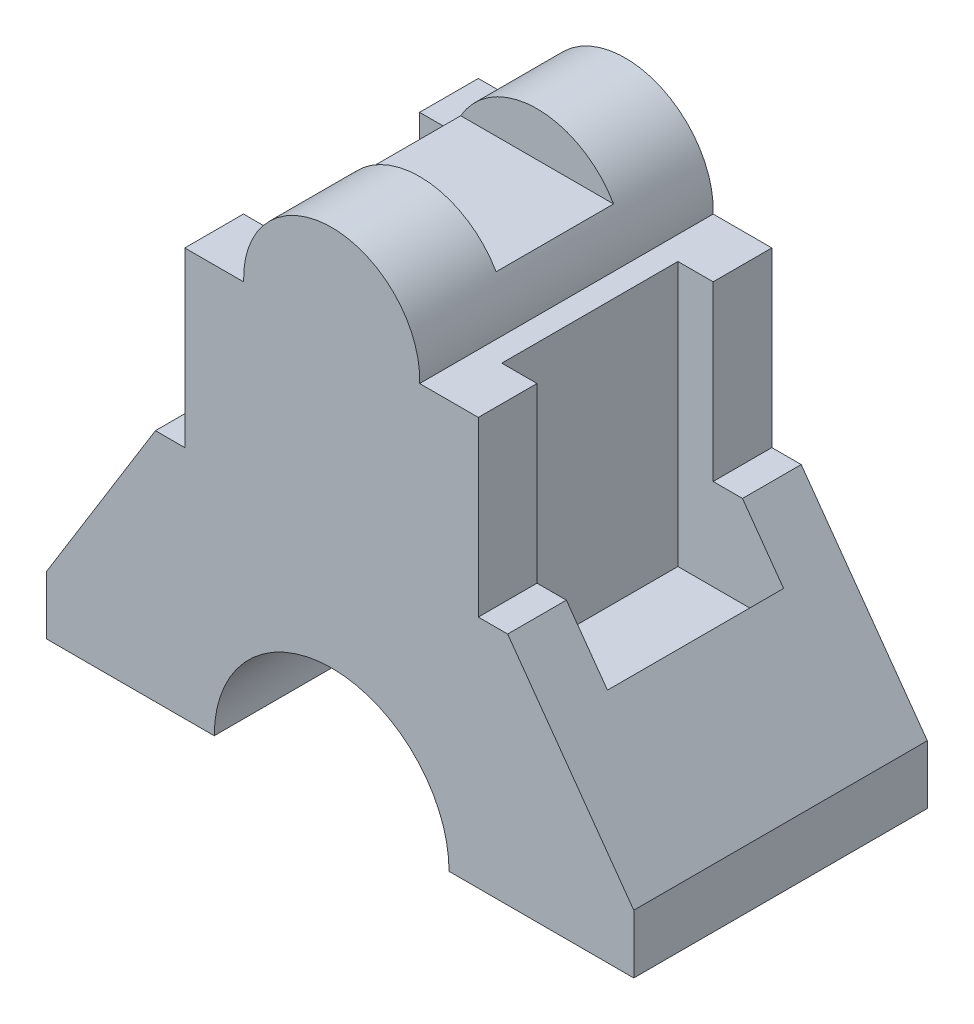
SolidWorks part; units mm, degrees
material "Aluminum Bronze"
ref_plane "Front Plane" through (0, 0, 0) normal (0, 0, 1) x (1, 0, 0)
ref_plane "Top Plane" through (0, 0, 0) normal (0, 1, 0) x (1, 0, 0)
ref_plane "Right Plane" through (0, 0, 0) normal (1, 0, 0) x (0, 0, -1)
sketch "Sketch1" plane through (0, 0, 0) normal (0, 0, 1) x (1, 0, 0)
  line L0 (35.7061, 0) -> (4.2453, 0)
  line L1 (-35.7547, 0) -> (-64.2939, 0)
  line L2 (-30.7449, 69.4581) -> (-40.7741, 69.4581)
  line L3 (1.5658, 10) -> (-15.7547, 10)
  line L4 (-44.0389, 10) -> (-64.2939, 10) construction
  line L6 (14.2259, 40) -> (9.2259, 40)
  line L8 (9.2259, 69.4581) -> (-0.7645, 69.4581)
  line L9 (-72.9873, 69.4581) -> (-72.9873, 69.4581) construction
  line L10 (-60.476, 40) -> (-64.2939, 40) construction
  line L11 (-15.7547, 0) -> (-15.7547, 20) construction
  line L12 (14.2259, 40) -> (35.7061, 10)
  line L13 (-45.7741, 40) -> (-64.2939, 10)
  line L14 (35.7061, 0) -> (35.7061, 10)
  line L15 (-64.2939, 0) -> (-64.2939, 10)
  line L16 (-40.7741, 40) -> (-45.7741, 40)
  line L17 (-40.7741, 40) -> (-40.7741, 69.4581)
  line L19 (9.2259, 40) -> (9.2259, 69.4581)
  line L21 (1.5658, 10) -> (-33.0752, 10)
  line L26 (35.7061, 10) -> (12.5296, 10) construction
  line L27 (35.7061, 40) -> (28.9667, 40) construction
  line L28 (41.0674, 69.7944) -> (41.0674, 69.7944) construction
  arc A0 (4.2453, 0) -> (-35.7547, 0) centre (-15.7547, 0) ccw
  arc A1 (-0.7645, 69.4581) -> (-30.7449, 69.4581) centre (-15.7547, 70) ccw
  arc A2 (12.5296, 10) -> (-44.0389, 10) centre (-15.7547, 0) ccw construction
  arc A4 (41.0674, 69.7944) -> (-72.9873, 69.4581) centre (-15.7547, 0) ccw construction
  arc A5 (28.9667, 40) -> (-60.476, 40) centre (-15.7547, 0) ccw construction
  point P4 (0, 0)
  point P24 (-15.7547, 0)
  point P25 (0, 0)
  dimension "D2" = 40
  dimension "D6" = 30
  dimension "D1" = 100
  dimension "D7" = 50
  dimension "D8" = 60
  dimension "D3" = 10
  dimension "D4" = 40
  dimension "D5" = 70
extrude "Boss-Extrude1" add sketch "Sketch1" along normal mid plane 50 contours L8 A1 L2 L17 L16 L13 L15 L1 A0 L0 L14 L12 L6 L19
sketch "Sketch3" plane through (0, 69.4581, 0) normal (0, 1, 0) x (1, 0, 0)
  line L0 (15.2259, 0) -> (9.2259, 0) construction
  line L2 (9.2259, -25) -> (9.2259, 25) construction
  line L3 (9.2259, 15) -> (9.2259, -15)
  line L4 (9.2259, -15) -> (3.2259, -15)
  line L6 (9.2259, 15) -> (3.2259, 15)
  line L7 (3.2259, -15) -> (3.2259, 15)
  line L8 (9.2259, 0) -> (3.2259, 15) construction
  line L9 (9.2259, 0) -> (3.2259, -15) construction
  line L11 (21.2259, 15) -> (9.2259, 15)
  line L12 (21.2259, 15) -> (21.2259, -15)
  line L13 (21.2259, -15) -> (9.2259, -15)
  line L15 (21.2259, 15) -> (9.2259, -15) construction
  line L16 (21.2259, -15) -> (9.2259, 15) construction
  line M8 (9.2259, -25) -> (9.2259, 25)
extrude "Cut-Extrude2" cut sketch "Sketch3" against normal blind 45 contours L7 L4 L6 M8 | L13 L12 L11 M8
ref_plane "Plane1" through (-14.2939, 0, 0) normal (-1, 0, 0) x (0, 0, 1)
mirror "Mirror1" about plane through (-14.2939, 0, 0) normal (-1, 0, 0) of "Cut-Extrude2"
ref_plane "Plane2" through (0, 84.4581, 0) normal (0, 1, 0) x (1, 0, 0)
sketch "Sketch4" plane through (0, 84.4581, 0) normal (0, 1, 0) x (1, 0, 0)
  line L1 (-36.6343, 10) -> (5.125, 10)
  line L2 (-36.6343, 10) -> (-36.6343, -10)
  line L3 (-36.6343, -10) -> (5.125, -10)
  line L4 (5.125, 10) -> (5.125, -10)
  line L5 (-36.6343, 10) -> (5.125, -10) construction
  line L6 (-36.6343, -10) -> (5.125, 10) construction
  line L8 (-31.8137, -15) -> (-31.8137, 15) construction
  point P0 (-15.7547, 0)
  point P9 (-31.8137, 0)
  dimension "D1" = 20
extrude "Cut-Extrude4" cut sketch "Sketch4" against normal mid plane 14
